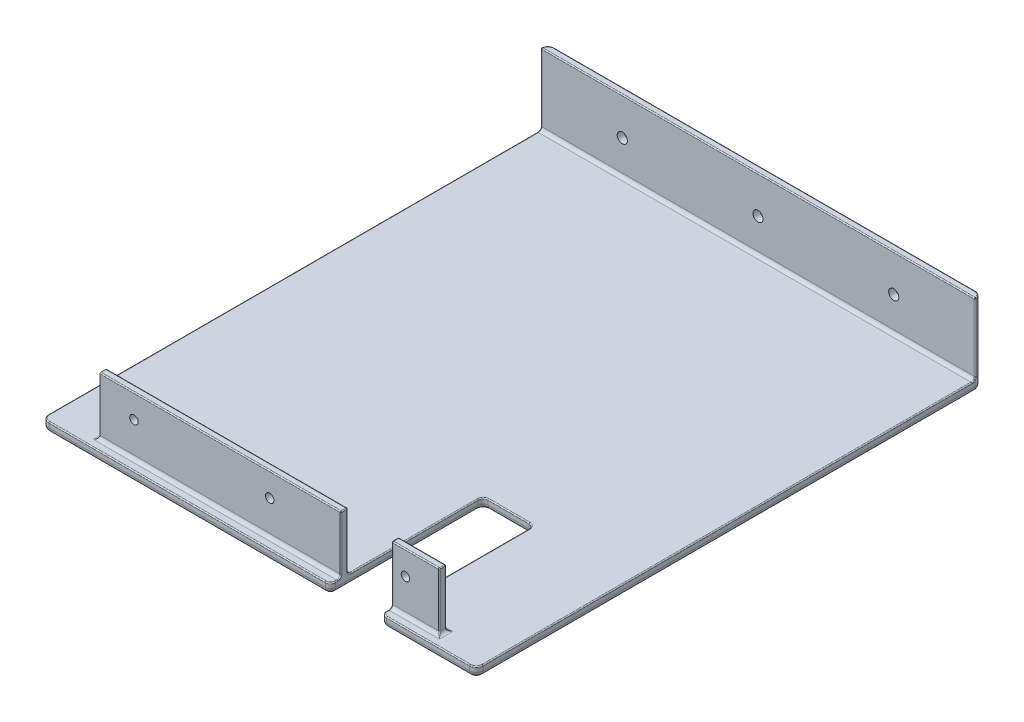
SolidWorks part; units mm, degrees
ref_plane "前视基准面" through (0, 0, 0) normal (0, 0, 1) x (1, 0, 0)
ref_plane "上视基准面" through (0, 0, 0) normal (0, 1, 0) x (1, 0, 0)
ref_plane "右视基准面" through (0, 0, 0) normal (1, 0, 0) x (0, 0, -1)
sketch "草图1" plane through (0, 0, 0) normal (0, 1, 0) x (1, 0, 0)
  line L1 (64, 74.5) -> (-64, 74.5)
  line L2 (64, 74.5) -> (64, -74.5)
  line L3 (64, -74.5) -> (-64, -74.5)
  line L4 (-64, 74.5) -> (-64, -74.5)
  line L5 (64, 74.5) -> (-64, -74.5) construction
  line L6 (64, -74.5) -> (-64, 74.5) construction
  point P0 (0, 0)
extrude "凸台-拉伸1" add sketch "草图1" along normal blind 3
sketch "草图3" plane through (0, 0, -74.5) normal (0, 0, -1) x (-1, 0, 0)
  line L1 (64, 0) -> (-64, 0)
  line L2 (64, 0) -> (64, 24)
  line L3 (64, 24) -> (-64, 24)
  line L4 (-64, 0) -> (-64, 24)
extrude "凸台-拉伸2" add sketch "草图3" against normal blind 2
sketch "草图4" plane through (0, 0, 74.5) normal (0, 0, 1) x (1, 0, 0)
  line L1 (50, 0) -> (-50, 0)
  line L2 (50, 0) -> (50, 20)
  line L3 (50, 20) -> (-50, 20)
  line L4 (-50, 0) -> (-50, 20)
  point P5 (0, 0)
  point P6 (0, 0)
  point P7 (0, 0)
  point P8 (0, 0)
  point P9 (0, 0)
extrude "凸台-拉伸3" add sketch "草图4" against normal blind 2 from offset 3.1 offset against normal yes
sketch "草图5" plane through (0, 0, 0) normal (0, -1, 0) x (1, 0, 0)
  line L0 (-64, 74.5) -> (64, 74.5) construction
  line L1 (36, 74.5) -> (21, 74.5)
  line L2 (36, 74.5) -> (36, 29.5)
  line L3 (36, 29.5) -> (21, 29.5)
  line L4 (21, 74.5) -> (21, 29.5)
  line L5 (64, 74.5) -> (64, -74.5) construction
  dimension "D1" = 28
  dimension "D2" = 45
extrude "切除-拉伸1" cut sketch "草图5" against normal up to next
sketch "草图6" plane through (0, 0, -74.5) normal (0, 0, -1) x (-1, 0, 0)
  line L0 (0, 0) -> (0, 32.2544) construction
  line L1 (-64, 0) -> (64, 0) construction
  circle A0 centre (40, 13) radius 1.5
  circle A1 centre (-40, 13) radius 1.5
  circle A2 centre (0, 13) radius 1.5
extrude "切除-拉伸2" cut sketch "草图6" against normal up to next
sketch "草图9" plane through (0, 0, 71.4) normal (0, 0, 1) x (1, 0, 0)
  line L0 (0, 14.2097) -> (0, 28.0264) construction
  circle A0 centre (40, 13) radius 1.5
  circle A1 centre (0, 13) radius 1.5
  circle A2 centre (-40, 13) radius 1.5
hole_wizard "M3 螺纹孔3" positions "草图12" profile "草图13" tap size "M3" standard "ISO" end condition up to next
sketch "草图12" plane through (0, 0, 71.4) normal (0, 0, 1) x (1, 0, 0)
  point P0 (40, 13)
  point P3 (0, 13)
  point P6 (-40, 13)
sketch "草图13" plane through (40, 13, 71.4) normal (1, 0, 0) x (0, -1, 0)
  line L0 (0, 0) -> (0, 2)
  line L1 (0, 2) -> (1.25, 2)
  line L2 (1.25, 2) -> (1.25, 0)
  line L5 (1.25, 0) -> (0, 0)
  line L11 (0, -6.35) -> (0, 107.95) construction
  dimension "通孔螺纹孔钻头直径" = 2.5
  dimension "通孔螺纹孔钻头深度" = 2
cosmetic thread "孔螺蚊线1" parameters "D2"=3
cosmetic thread "孔螺蚊线2" parameters "D2"=3
cosmetic thread "孔螺蚊线3" parameters "D2"=3
fillet "圆角4" radius 2 4 edges at (64, 12, -74.5) (-64, 12, -74.5) (-64, 1.5, 74.5) (64, 1.5, 74.5)
fillet "圆角1" radius 1.5 16 edges at (49, 0, 74.5) (64, 0, 0) (0, 0, -74.5) (-64, 0, 0) (-20.5, 0, 74.5) (21, 0, 52) (28.5, 0, 29.5) (36, 0, 52) (21, 1.5, 29.5) (36, 1.5, 29.5) (36, 1.5, 74.5) (21, 1.5, 74.5) (-63.4142, 0, -73.9142) (-63.4142, 0, 73.9142) (63.4142, 0, 73.9142) (63.4142, 0, -73.9142)
fillet "圆角2" radius 1 7 edges at (50, 3, 70.4) (0, 3, -72.5) (-14.5, 3, 71.4) (43, 3, 71.4) (43, 3, 69.4) (-50, 3, 70.4) (-14.5, 3, 69.4)
fillet "圆角3" radius 0.3 42 edges at (36, 12, 69.4) (36, 3.2929, 69.1071) (36, 3, 49.7) (35.5607, 3, 29.9393) (28.5, 3, 29.5) (21.4393, 3, 29.9393) (21, 3, 49.7) (21, 3.2929, 69.1071) (-64, 3.2929, -72.2071) (-64, 3, 0.5) (-21.25, 3, 74.5) (20.5607, 3, 74.0607) (21, 3, 72.7) (21, 3.2929, 71.6929) (64, 3.2929, -72.2071) (64, 3, 0.5) (49.75, 3, 74.5) (36.4393, 3, 74.0607) (36, 3, 72.7) (36, 3.2929, 71.6929) (50.2929, 3.2929, 69.1071) (50.2929, 3.2929, 71.6929) (21, 20, 70.4) (36, 20, 70.4) (50, 20, 70.4) (-14.5, 20, 69.4) (-14.5, 20, 71.4) (21, 12, 69.4) (21, 12, 71.4) (43, 20, 69.4) (36, 12, 71.4) (43, 20, 71.4) (50, 12, 69.4) (50, 12, 71.4) (0, 24, -72.5) (0, 24, -74.5) (-63.4142, 24, -73.9142) (63.4142, 24, -73.9142) (-64, 14, -72.5) (-63.4142, 3, 73.9142) (64, 14, -72.5) (63.4142, 3, 73.9142)
